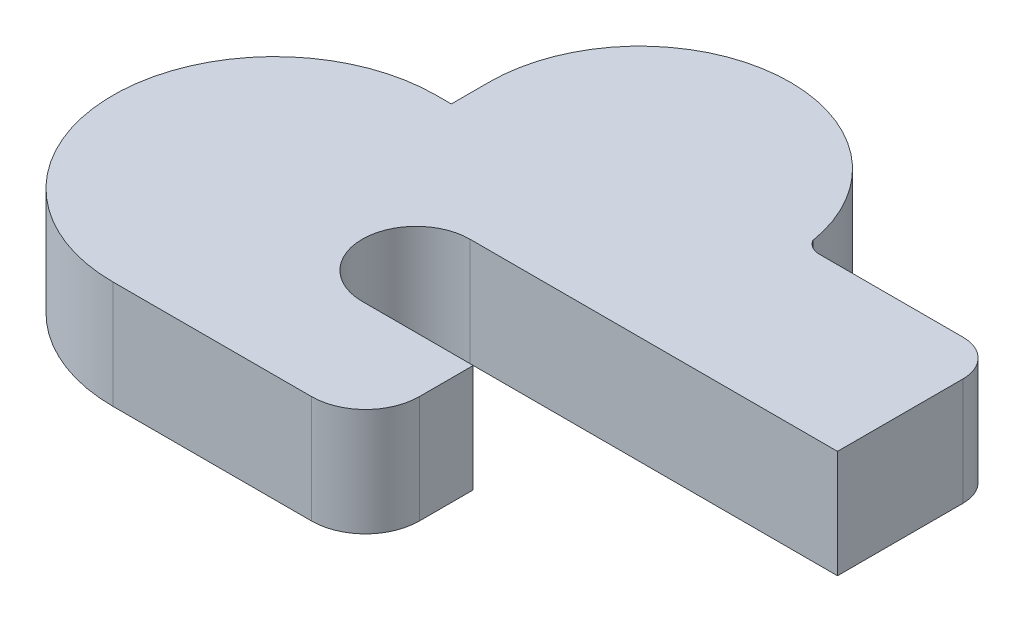
SolidWorks part; units mm, degrees
ref_plane "Front Plane" through (0, 0, 0) normal (0, 0, 1) x (1, 0, 0)
ref_plane "Top Plane" through (0, 0, 0) normal (0, 1, 0) x (1, 0, 0)
ref_plane "Right Plane" through (0, 0, 0) normal (1, 0, 0) x (0, 0, -1)
sketch "Sketch1" plane through (0, 0, 0) normal (0, 1, 0) x (1, 0, 0)
  line L0 (0, 0) -> (-3.09, 0)
  line L1 (-3.09, 3) -> (7.14, 3)
  line L2 (7.14, 3) -> (7.14, 6.5)
  line L6 (-6.61, 7.0541) -> (-6.61, 6)
  line L7 (-6.61, 6) -> (-7.03, 6)
  line L9 (0, -1.5) -> (0, 0)
  line L10 (-7.0309, -3) -> (-1.5, -3)
  line L11 (2.14, 7.5) -> (6.14, 7.5)
  arc A0 (-3.09, 0) -> (-3.09, 3) centre (-3.09, 1.5) cw
  arc A1 (7.14, 6.5) -> (6.14, 7.5) centre (6.14, 6.5) ccw
  arc A4 (1.7137, 7.7387) -> (-6.61, 7.0541) centre (-2.42, 7.0541) ccw
  arc A5 (-7.03, 6) -> (-7.0309, -3) centre (-7.03, 1.5) ccw
  arc A9 (2.14, 7.5) -> (1.7137, 7.7387) centre (2.14, 8) cw
  arc A10 (-1.5, -3) -> (0, -1.5) centre (-1.5, -1.5) ccw
  point P12 (-2.7635, 11.23)
  point P14 (-6.0452, 6)
  point P17 (-3.09, 8.4197)
  point P19 (0, 0)
  point P23 (-3.09, 8.4197)
  point P26 (0.4135, 10.5523)
  point P27 (1.6964, 7.8404)
  point P29 (-1.5, 6)
  point P43 (-11.53, 1.5004)
  point P44 (-4.59, 1.5)
  dimension "10.9" = 4.5
  dimension "D4" = 1.5
  dimension "D5" = 14.17
  dimension "D6" = 4.19
  dimension "3" = 1
  dimension "D7" = 0.5
  dimension "D10" = 5.5309
  dimension "D11" = 1.5
  dimension "D2" = 14.23
  dimension "D3" = 13.75
  dimension "3.65" = 4.5
  dimension "D8" = 6.94
  dimension "D9" = 3.09
  dimension "5" = 5
extrude "Boss-Extrude2" add sketch "Sketch1" along normal blind 3
